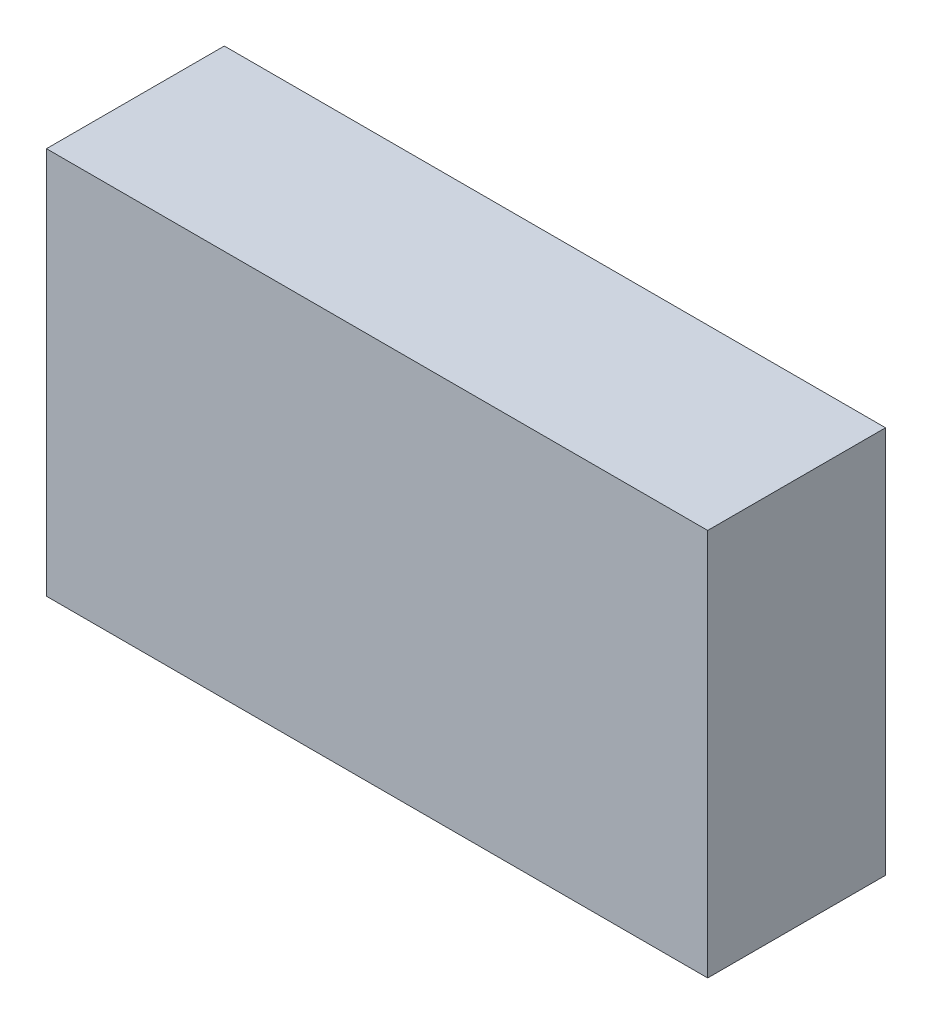
SolidWorks part; units mm, degrees
ref_plane "Front Plane" through (0, 0, 0) normal (0, 0, 1) x (1, 0, 0)
ref_plane "Top Plane" through (0, 0, 0) normal (0, 1, 0) x (1, 0, 0)
ref_plane "Right Plane" through (0, 0, 0) normal (1, 0, 0) x (0, 0, -1)
sketch "Sketch1" plane through (0, 0, 0) normal (0, 0, 1) x (1, 0, 0)
  line L1 (-29, -17) -> (29, -17)
  line L2 (-29, -17) -> (-29, 17)
  line L3 (-29, 17) -> (29, 17)
  line L4 (29, -17) -> (29, 17)
  line L5 (-29, -17) -> (29, 17) construction
  line L6 (-29, 17) -> (29, -17) construction
  point P0 (0, 0)
extrude "Envelope" add sketch "Sketch1" along normal blind 15.6
